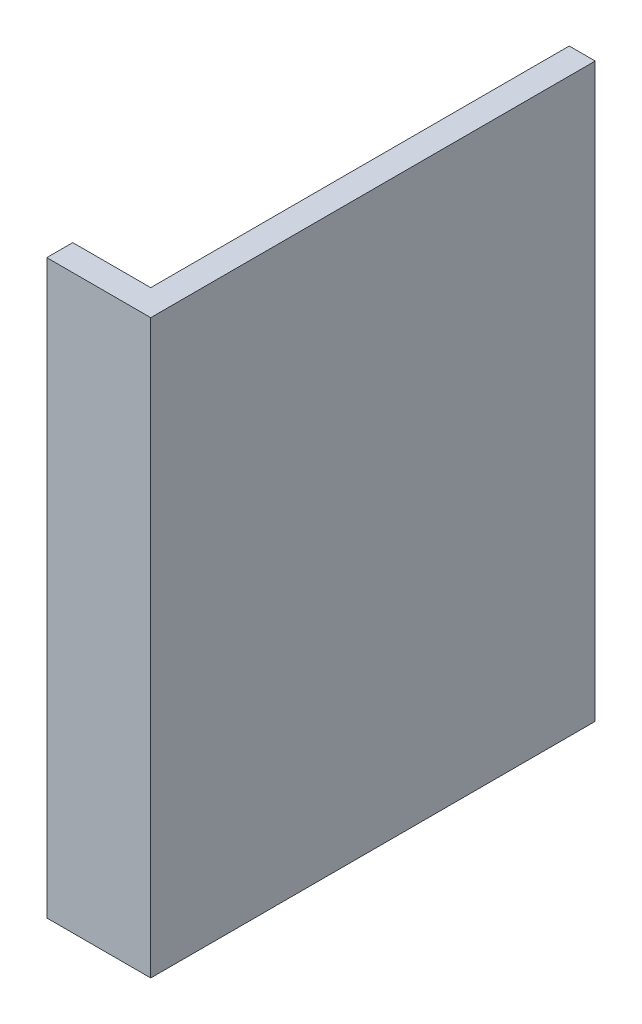
SolidWorks part; units mm, degrees
ref_plane "Front Plane" through (0, 0, 0) normal (0, 0, 1) x (1, 0, 0)
ref_plane "Top Plane" through (0, 0, 0) normal (0, 1, 0) x (1, 0, 0)
ref_plane "Right Plane" through (0, 0, 0) normal (1, 0, 0) x (0, 0, -1)
sketch "Sketch1" plane through (0, 0, 0) normal (0, 1, 0) x (1, 0, 0)
  line L0 (-2, 0) -> (0, 0)
  line L1 (0, 0) -> (0, 8.55)
  line L2 (0, 8.55) -> (-0.5, 8.55)
  line L3 (-0.5, 8.55) -> (-0.5, 0.5)
  line L4 (-0.5, 0.5) -> (-2, 0.5)
  line L5 (-2, 0.5) -> (-2, 0)
  dimension "D1" = 8.55
  dimension "D2" = 2
  dimension "D3" = 0.5
  dimension "D4" = 0.5
extrude "Boss-Extrude1" add sketch "Sketch1" along normal blind 11
